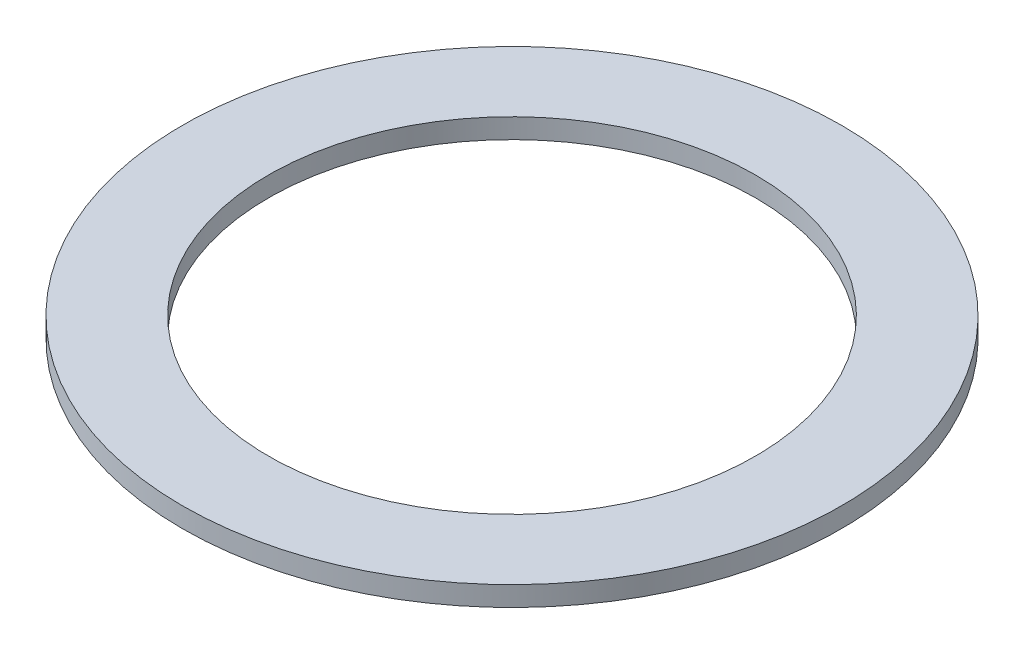
SolidWorks part; units mm, degrees
ref_plane "Front Plane" through (0, 0, 0) normal (0, 0, 1) x (1, 0, 0)
ref_plane "Top Plane" through (0, 0, 0) normal (0, 1, 0) x (1, 0, 0)
ref_plane "Right Plane" through (0, 0, 0) normal (1, 0, 0) x (0, 0, -1)
sketch "Sketch1" plane through (0, 0, 0) normal (0, 0, 1) x (1, 0, 0)
  line L0 (-18.4, 0) -> (-24.9, 0)
  line L1 (-18.4, 0) -> (-18.4, 1.5)
  line L2 (-18.4, 1.5) -> (-24.9, 1.5)
  line L3 (-24.9, 1.5) -> (-24.9, 0)
  line L5 (0, 0) -> (0, 25.1875) construction
  dimension "D1" = 18.4
  dimension "D2" = 6.5
  dimension "D3" = 1.5
revolve "Revolve1" add sketch "Sketch1" angle 360 about L5
